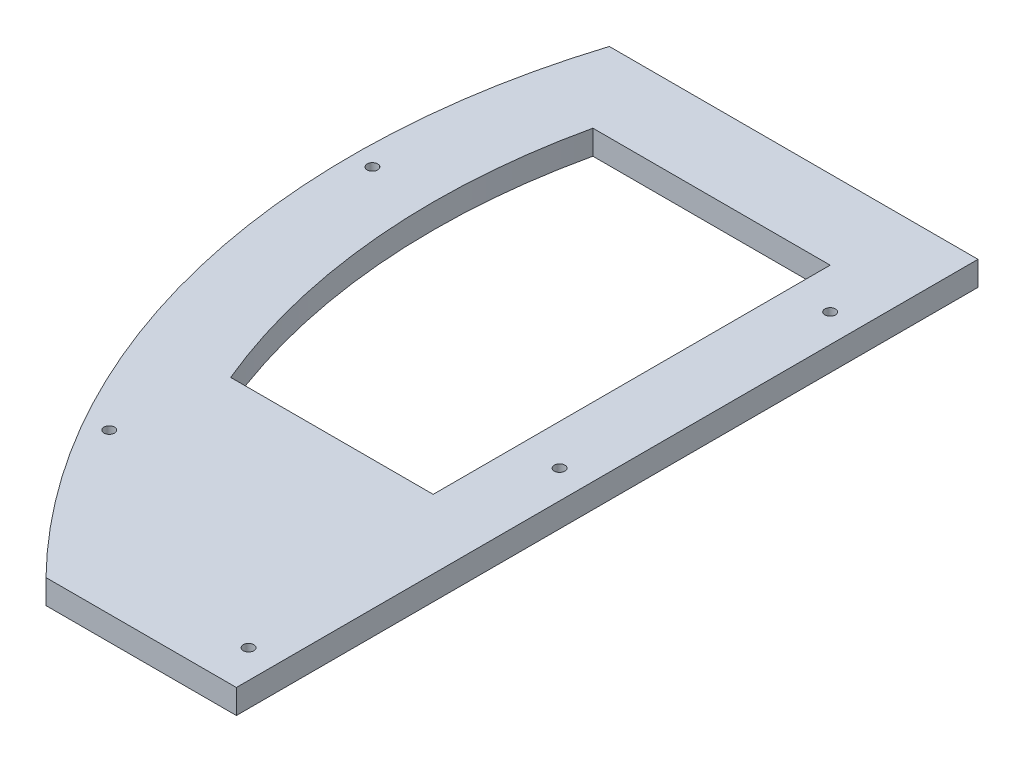
SolidWorks part; units mm, degrees
ref_plane "Front Plane" through (0, 0, 0) normal (0, 0, 1) x (1, 0, 0)
ref_plane "Top Plane" through (0, 0, 0) normal (0, 1, 0) x (1, 0, 0)
ref_plane "Right Plane" through (0, 0, 0) normal (1, 0, 0) x (0, 0, -1)
sketch "Sketch1" plane through (0, 0, 0) normal (0, 1, 0) x (1, 0, 0)
  line L0 (0, 0) -> (0, -162.5) construction
  line L2 (-100, -144.5) -> (100, -144.5)
  line L3 (-100, -144.5) -> (-100, 35.5)
  line L4 (-100, 35.5) -> (100, 35.5)
  line L5 (100, -144.5) -> (100, 35.5)
  line L6 (-100, -144.5) -> (100, 35.5) construction
  line L7 (-100, 35.5) -> (100, -144.5) construction
  circle A0 centre (0, 0) radius 162.5
  point P4 (0, -54.5)
  dimension "D1" = 325
  dimension "D2" = 180
  dimension "D3" = 35.5
  dimension "D4" = 200
sketch "Sketch2" plane through (0, 0, 0) normal (0, 1, 0) x (1, 0, 0)
  line L0 (-100, -144.5) -> (-100, 35.5) construction
  line L1 (-100, 35.5) -> (100, 35.5) construction
  line L2 (100, -144.5) -> (100, 35.5) construction
  line L3 (-100, -128.0869) -> (-100, 35.5)
  line L4 (-100, 35.5) -> (100, 35.5)
  line L5 (100, -128.0869) -> (100, 35.5)
  circle A0 centre (0, 0) radius 162.5 construction
  arc A1 (100, -128.0869) -> (-100, -128.0869) centre (0, 0) ccw
extrude "Boss-Extrude1" add sketch "Sketch2" along normal blind 6
sketch "Sketch4" plane through (0, 6, 0) normal (0, 1, 0) x (1, 0, 0)
  line L0 (0, 0) -> (0, 162.5) construction
  line L1 (119.15, -101.1581) -> (123.8764, -105.1708) construction
  line L2 (100, 35.5) -> (100, -128.0869) construction
  line L4 (-100, 35.5) -> (100, 35.5) construction
  arc A0 (100, -128.0869) -> (-100, -128.0869) centre (0, 0) ccw construction
  circle A1 centre (119.15, -101.1581) radius 1
  circle A2 centre (87.75, 86.5) radius 1
  circle A3 centre (152, 23.5891) radius 1
  circle A4 centre (-87.75, 86.5) radius 1
  circle A5 centre (99, 36.6) radius 1
  circle A6 centre (-99, 36.6) radius 1
  circle A7 centre (-152, 23.5891) radius 1
  circle A8 centre (-119.15, -101.1581) radius 1
  dimension "D1" = 2
  dimension "D3" = 6.2
  dimension "D2" = 129
  dimension "D4" = 19.15
  dimension "D5" = 52
  dimension "D6" = 51
  dimension "D7" = 87.75
  dimension "D8" = 1.1
extrude "Cut-Extrude2" [suppressed] cut sketch "Sketch4" against normal through all
sketch "Sketch5" plane through (0, 6, 0) normal (0, 1, 0) x (1, 0, 0)
  line L0 (-100, -128.0869) -> (-100, 35.5) construction
  line L1 (-100, -108.0869) -> (100, -108.0869)
  line L2 (-100, -108.0869) -> (-100, -128.0869)
  line L3 (-100, -128.0869) -> (100, -128.0869)
  line L4 (100, -108.0869) -> (100, -128.0869)
  dimension "D1" = 20
extrude "Boss-Extrude2" add sketch "Sketch5" against normal blind 6
sketch "Sketch6" plane through (0, 6, 0) normal (0, 1, 0) x (1, 0, 0)
  line L0 (0, 0) -> (0, -108.0869) construction
  line L1 (100, -108.0869) -> (-100, -108.0869) construction
  line L2 (-100, 35.5) -> (100, 35.5) construction
  line L4 (-13.5, -108.0869) -> (-13.5, 35.5)
  line L5 (-13.5, -108.0869) -> (-100, -108.0869)
  line L6 (13.5, -108.0869) -> (13.5, 35.5)
  line L7 (-13.5, -108.0869) -> (13.5, 35.5) construction
  line L8 (-13.5, 35.5) -> (13.5, -108.0869) construction
  line L9 (-100, -108.0869) -> (-100, 35.5) construction
  line L10 (-100, -108.0869) -> (-100, 35.5)
  line L11 (100, -108.0869) -> (13.5, -108.0869)
  line L12 (-13.5, 35.5) -> (-100, 35.5)
  line L13 (-100, -108.0869) -> (100, -108.0869)
  line L14 (-100, 35.5) -> (-100, -108.0869)
  line L15 (100, 35.5) -> (-100, 35.5)
  line L16 (100, -108.0869) -> (100, 35.5)
  line L17 (-100, -108.0869) -> (-13.5, -108.0869)
  line L18 (-100, 35.5) -> (-100, -108.0869)
  line L19 (100, 35.5) -> (13.5, 35.5)
  line L20 (100, -108.0869) -> (100, 35.5)
  line L21 (13.5, -108.0869) -> (100, -108.0869)
  point P5 (0, -36.2934)
  line M5 (100, -108.0869) -> (-100, -108.0869)
  line M6 (-100, -108.0869) -> (-100, 35.5)
  line M7 (-100, 35.5) -> (100, 35.5)
  line M8 (100, 35.5) -> (100, -108.0869)
  dimension "D1" = 27
  dimension "D2" = 0
extrude "Boss-Extrude3" add sketch "Sketch6" against normal through all contours L4 M5 M7 M6 | L6 M5 M8 M7
sketch "Sketch7" plane through (0, 6, 0) normal (0, 1, 0) x (1, 0, 0)
  line L0 (-150, -62.5) -> (-100, -62.5)
  line L1 (-100, -144.5) -> (-100, 35.5) construction
  line L2 (-158.5749, 35.5) -> (-100, 35.5)
  line L3 (-100, 35.5) -> (-100, -62.5)
  line L4 (0, 0) -> (0, -162.5) construction
  line L5 (100, 35.5) -> (100, -62.5)
  line L6 (158.5749, 35.5) -> (100, 35.5)
  line L7 (150, -62.5) -> (100, -62.5)
  line L8 (-100, 35.5) -> (100, 35.5) construction
  arc A0 (100, -128.0869) -> (-100, -128.0869) centre (0, 0) ccw construction
  circle A1 centre (0, 0) radius 162.5 construction
  arc A2 (-158.5749, 35.5) -> (-150, -62.5) centre (0, 0) ccw
  arc A3 (158.5749, 35.5) -> (150, -62.5) centre (0, 0) cw
  dimension "D1" = 50
extrude "Cut-Extrude3" cut sketch "Sketch7" against normal through all
sketch "Sketch8" plane through (0, 6, 0) normal (0, 1, 0) x (1, 0, 0)
  line L0 (0, 162.5) -> (0, 0) construction
  line L1 (-30, 132.5) -> (-30, 159.7068)
  line L2 (30, 132.5) -> (30, 159.7068)
  arc A0 (-30, 132.5) -> (30, 132.5) centre (0, 132.5) ccw
  circle A1 centre (0, 0) radius 162.5 construction
  arc A2 (30, 159.7068) -> (-30, 159.7068) centre (0, 0) ccw
  dimension "D1" = 60
extrude "Cut-Extrude4" cut sketch "Sketch8" against normal through all
sketch "Sketch9" plane through (0, 6, 0) normal (0, 1, 0) x (1, 0, 0)
  line L0 (0, 0) -> (0, 162.5) construction
  line L1 (-105, 107) -> (105, 107)
  line L2 (-105, 107) -> (-105, 55)
  line L3 (-105, 55) -> (105, 55)
  line L4 (105, 107) -> (105, 55)
  line L5 (-105, 107) -> (105, 55) construction
  line L6 (-105, 55) -> (105, 107) construction
  line L7 (-100, 35.5) -> (100, 35.5) construction
  circle A0 centre (0, 0) radius 162.5 construction
  point P0 (0, 81)
  dimension "D1" = 52
  dimension "D2" = 210
  dimension "D3" = 19.5
extrude "Cut-Extrude5" cut sketch "Sketch9" against normal through all
sketch "Sketch10" plane through (0, 6, 0) normal (0, 1, 0) x (1, 0, 0)
  line L0 (-100, -128.0869) -> (-130, -128.0869)
  line L1 (100, -128.0869) -> (130, -128.0869)
  arc A0 (130, -128.0869) -> (-130, -128.0869) centre (0, 0) ccw
  circle A1 centre (0, 0) radius 162.5 construction
  arc A2 (100, -128.0869) -> (-100, -128.0869) centre (0, 0) ccw
  dimension "D1" = 20
extrude "Boss-Extrude4" add sketch "Sketch10" against normal through all
fillet "Fillet1" radius 10 4 edges at (105, 3, -107) (105, 3, -55) (-105, 3, -55) (-105, 3, -107)
sketch "Sketch11" plane through (0, 6, 0) normal (0, 1, 0) x (1, 0, 0)
  line L0 (0, 182.5) -> (0, 162.5) construction
  arc A1 (130, -128.0869) -> (-130, -128.0869) centre (0, 0) ccw construction
  arc A2 (30, 159.7068) -> (-30, 159.7068) centre (0, 0) ccw construction
  circle A3 centre (0, 177.5) radius 1.3
  circle A4 centre (88.75, 153.7195) radius 1.3
  circle A5 centre (153.7195, 88.75) radius 1.3
  circle A6 centre (177.5, 0) radius 1.3
  circle A7 centre (153.7195, -88.75) radius 1.3
  circle A8 centre (88.75, -153.7195) radius 1.3
  circle A9 centre (0, -177.5) radius 1.3
  circle A10 centre (-88.75, -153.7195) radius 1.3
  circle A11 centre (-153.7195, -88.75) radius 1.3
  circle A12 centre (-177.5, 0) radius 1.3
  circle A13 centre (-153.7195, 88.75) radius 1.3
  circle A14 centre (-88.75, 153.7195) radius 1.3
  point P36 (0, 0)
  dimension "D1" = 2.6
  dimension "D3" = 5
  dimension "D2" = 12
extrude "Cut-Extrude6" cut sketch "Sketch11" against normal through all
sketch "Sketch12" plane through (0, 6, 0) normal (0, 1, 0) x (1, 0, 0)
  line L0 (-139.1465, -118.0869) -> (139.1465, -118.0869) construction
  line L1 (-130, -128.0869) -> (130, -128.0869) construction
  line L2 (-100, -144.5) -> (-100, 35.5) construction
  line L3 (100, -144.5) -> (100, 35.5) construction
  line L4 (-90, -118.0869) -> (-90, 35.5) construction
  line L5 (0, 0) -> (0, -118.0869) construction
  line L6 (-100, 35.5) -> (100, 35.5) construction
  arc A0 (130, -128.0869) -> (-130, -128.0869) centre (0, 0) ccw construction
  circle A1 centre (0, -118.0869) radius 1.3
  circle A2 centre (-90, -118.0869) radius 1.3
  circle A3 centre (90, -118.0869) radius 1.3
  circle A4 centre (-90, 25.5) radius 1.3
  circle A5 centre (-90, -41.2934) radius 1.3
  circle A6 centre (90, -41.2934) radius 1.3
  circle A7 centre (90, 25.5) radius 1.3
  dimension "D2" = 2.6
  dimension "D1" = 10
  dimension "D3" = 10
  dimension "D4" = 10
  dimension "D5" = 10
extrude "Cut-Extrude7" cut sketch "Sketch12" against normal through all
sketch "Sketch13" plane through (0, 6, 0) normal (0, 1, 0) x (1, 0, 0)
  line L0 (0, 0) -> (0, 35.5) construction
  line L1 (-13.5, 35.5) -> (13.5, 35.5) construction
  circle A0 centre (-17.875, -13.5) radius 1.75
  circle A1 centre (17.875, -13.5) radius 1.75
  dimension "D3" = 3.5
  dimension "D1" = 35.75
  dimension "D2" = 13.5
extrude "Cut-Extrude8" cut sketch "Sketch13" against normal blind 10
sketch "Sketch14" plane through (0, 6, 0) normal (0, 1, 0) x (1, 0, 0)
  line L0 (-15.8035, 107) -> (-95, 107) construction
  line L1 (0, 0) -> (0, 162.5) construction
  line L2 (-30, 132.5) -> (30, 132.5)
  line L3 (55.5, 107) -> (-55.5, 107)
  line L4 (-30, 159.7068) -> (-30, 132.5) construction
  arc A0 (-30, 132.5) -> (-55.5, 107) centre (-55.5, 132.5) cw
  arc A1 (30, 159.7068) -> (-30, 159.7068) centre (0, 0) ccw construction
  arc A2 (30, 132.5) -> (55.5, 107) centre (55.5, 132.5) ccw
extrude "Cut-Extrude9" cut sketch "Sketch14" against normal through all
sketch "Sketch15" plane through (0, 6, 0) normal (0, 1, 0) x (1, 0, 0)
  line L0 (-95, 55) -> (-174.0151, 55)
  line L1 (-83, 55) -> (-83, -128.0869)
  line L2 (-95, 55) -> (95, 55) construction
  line L3 (-130, -128.0869) -> (130, -128.0869) construction
  line L4 (-130, -128.0869) -> (-83, -128.0869)
  line L5 (-95, 55) -> (-83, 55)
  arc A0 (130, -128.0869) -> (-130, -128.0869) centre (0, 0) ccw construction
  arc A1 (-174.0151, 55) -> (-130, -128.0869) centre (0, 0) ccw
  circle A2 centre (0, 0) radius 208.6527
  dimension "D1" = 12
extrude "Cut-Extrude10" cut sketch "Sketch15" against normal through all
